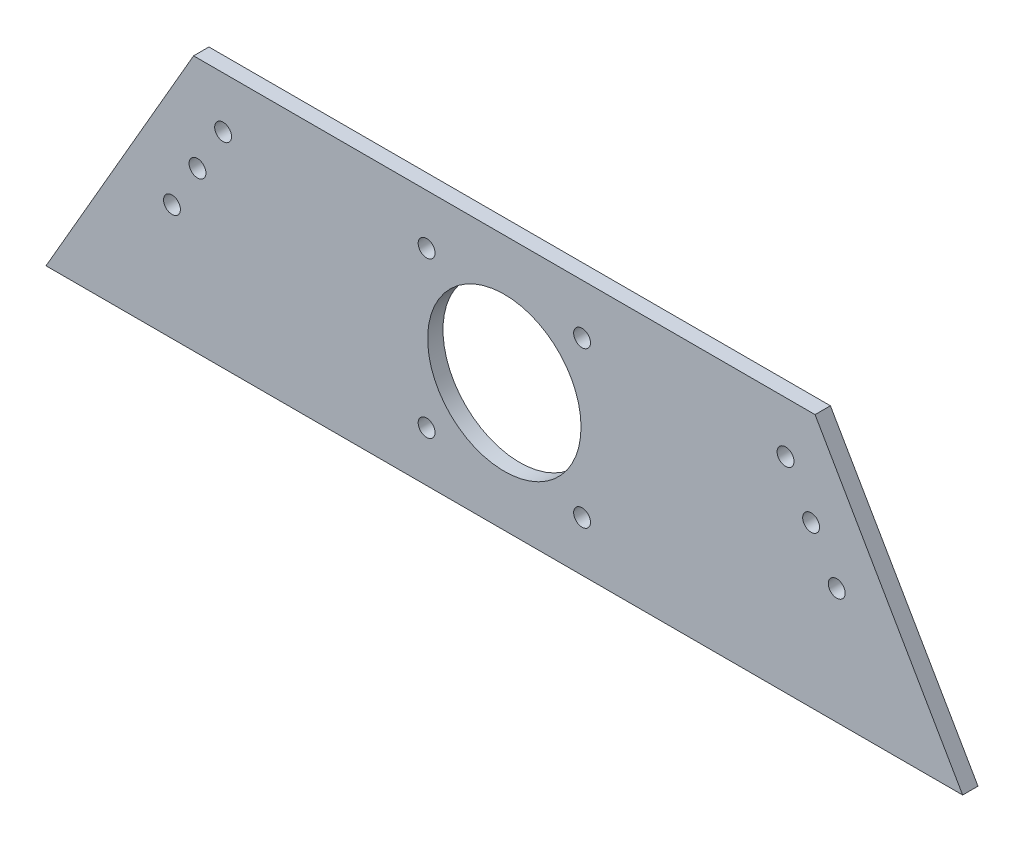
SolidWorks part; units mm, degrees
ref_plane "前视基准面" through (0, 0, 0) normal (0, 0, 1) x (1, 0, 0)
ref_plane "上视基准面" through (0, 0, 0) normal (0, 1, 0) x (1, 0, 0)
ref_plane "右视基准面" through (0, 0, 0) normal (1, 0, 0) x (0, 0, -1)
other "Configuration Table"
sketch "草图1" plane through (0, 0, 0) normal (0, 0, 1) x (1, 0, 0)
  line L1 (-65, -10) -> (65, -10)
  line L2 (-65, -10) -> (-65, 10)
  line L3 (-65, 10) -> (65, 10)
  line L4 (65, -10) -> (65, 10)
  line L5 (-65, -10) -> (65, 10) construction
  line L6 (-65, 10) -> (65, -10) construction
  circle A0 centre (-55, 0) radius 1.65
  circle A1 centre (55, 0) radius 1.65
  point P0 (0, 0)
  dimension "D3" = 3.3
  dimension "D4" = 3.3
  dimension "D1" = 130
  dimension "D2" = 20
  dimension "D5" = 10
  dimension "D6" = 10
extrude "凸台-拉伸1" add sketch "草图1" along normal blind 3
sketch "草图2" plane through (0, 0, 3) normal (0, 0, 1) x (1, 0, 0)
  line L5 (-65, -10) -> (65, -10)
  line L6 (-65, -10) -> (-65, -40)
  line L7 (-65, -40) -> (65, -40)
  line L8 (65, -10) -> (65, -40)
  dimension "D1" = 130
  dimension "D2" = 30
extrude "凸台-拉伸2" add sketch "草图2" against normal blind 3
sketch "草图3" plane through (0, 0, 0) normal (0, 0, 1) x (1, 0, 0)
  line L0 (65, 10) -> (-65, 10) construction
  line L1 (0, -15) -> (-25, 10) construction
  line L2 (0, 0) -> (0, -30) construction
  line L3 (-15, -15) -> (0, -15) construction
  circle A0 centre (0, -15) radius 15
  circle A1 centre (0, -15) radius 21.5 construction
  circle A2 centre (-15.2028, 0.2028) radius 1.65
  circle A3 centre (-15.2028, -30.2028) radius 1.65
  circle A4 centre (15.2028, -30.2028) radius 1.65
  circle A5 centre (15.2028, 0.2028) radius 1.65
  point P5 (-15.2028, 0.2028)
  dimension "D2" = 30
  dimension "D3" = 43
  dimension "D5" = 3.3
  dimension "D1" = 25
  dimension "D4" = 45
extrude "切除-拉伸1" cut sketch "草图3" along normal blind 3
sketch "草图4" plane through (0, 0, 0) normal (0, 0, 1) x (1, 0, 0)
  line L0 (65, 10) -> (60.77, 10)
  line L1 (65, 10) -> (-65, 10) construction
  line L2 (60.77, 10) -> (65, 2.6734)
  line L3 (65, -40) -> (65, 10) construction
  line L4 (65, 2.6734) -> (65, 10)
  line L5 (0, 10) -> (0, -40) construction
  line L6 (-65, -40) -> (65, -40) construction
  line L7 (-65, 2.6734) -> (-65, 10)
  line L8 (-60.77, 10) -> (-65, 2.6734)
  line L9 (-65, 10) -> (-60.77, 10)
  dimension "D1" = 4.23
  dimension "D2" = 60
extrude "切除-拉伸2" cut sketch "草图4" along normal blind 3
sketch "草图5" plane through (0, 0, 3) normal (0, 0, 1) x (1, 0, 0)
  line L0 (-65, 2.6734) -> (-89.6375, -40)
  line L1 (-89.6375, -40) -> (-65, -40)
  line L2 (-65, -40) -> (-65, 2.6734)
  line L3 (0, 0) -> (0, -30) construction
  line L4 (89.6375, -40) -> (65, -40)
  line L5 (65, 2.6734) -> (89.6375, -40)
  line L6 (65, -40) -> (65, 2.6734)
  circle A0 centre (0, -15) radius 15 construction
  dimension "D1" = 30
extrude "凸台-拉伸3" add sketch "草图5" against normal blind 3
sketch "草图6" plane through (0, 0, 0) normal (0, 0, -1) x (-1, 0, 0)
  line L0 (-55, 0) -> (-78.094, -40) construction
  line L1 (89.6375, -40) -> (-89.6375, -40) construction
  line L2 (0, 0) -> (0, -30) construction
  circle A0 centre (-60, -8.6603) radius 1.65
  circle A1 centre (-65, -17.3205) radius 1.65
  circle A2 centre (0, -15) radius 15 construction
  circle A3 centre (65, -17.3205) radius 1.65
  circle A4 centre (60, -8.6603) radius 1.65
  dimension "D2" = 3.3
  dimension "D3" = 3.3
  dimension "D1" = 60
  dimension "D4" = 10
  dimension "D5" = 10
extrude "切除-拉伸3" cut sketch "草图6" against normal blind 3
